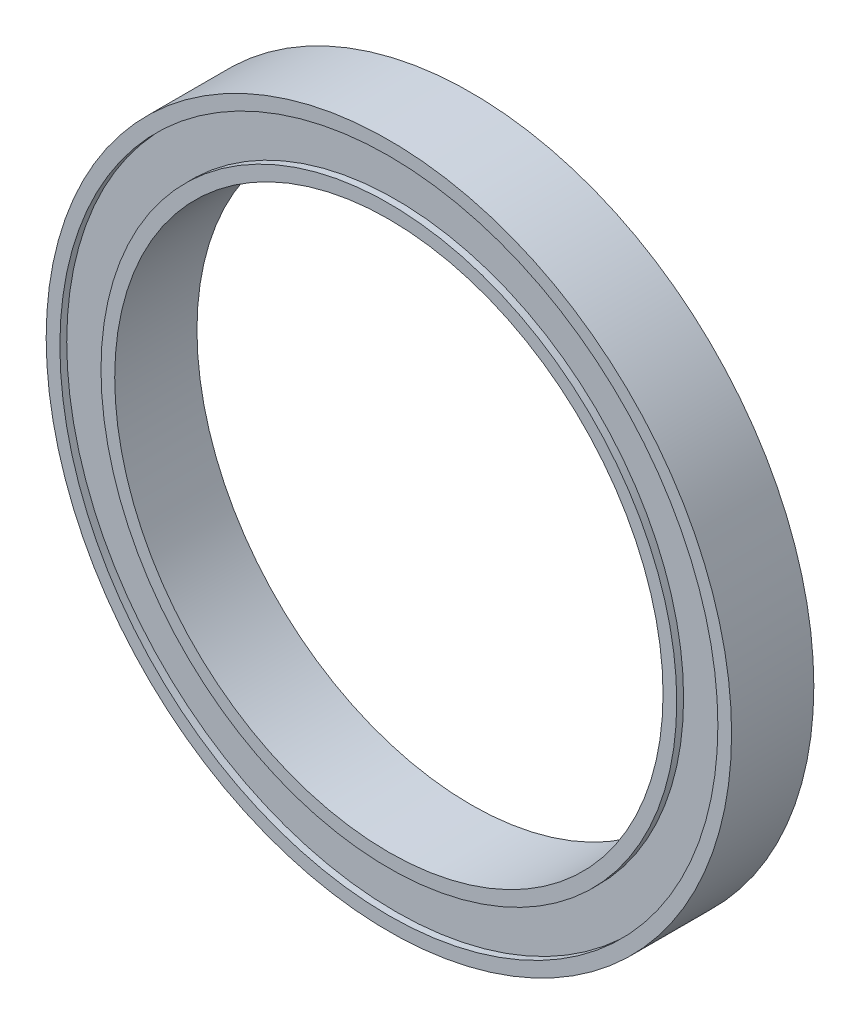
SolidWorks part; units mm, degrees
material "Plain Carbon Steel"
ref_plane "Front Plane" through (0, 0, 0) normal (0, 0, 1) x (1, 0, 0)
ref_plane "Top Plane" through (0, 0, 0) normal (0, 1, 0) x (1, 0, 0)
ref_plane "Right Plane" through (0, 0, 0) normal (1, 0, 0) x (0, 0, -1)
sketch "Sketch1" plane through (0, 0, 0) normal (1, 0, 0) x (0, 0, -1)
  line L0 (0, 0) -> (0, 22.5) construction
  line L1 (0, 0) -> (3, 0) construction
  line L2 (-3, 20) -> (3, 20)
  line L3 (-3, 20) -> (-3, 25)
  line L4 (-3, 25) -> (3, 25)
  line L5 (3, 20) -> (3, 25)
  line L6 (-3, 20) -> (3, 25) construction
  line L7 (-3, 25) -> (3, 20) construction
  dimension "D1" = 20
  dimension "D2" = 25
  dimension "D3" = 6
  dimension "D4" = 5
revolve "Revolve1" add sketch "Sketch1" angle 360 about L1
sketch "Sketch3" plane through (0, 0, 0) normal (1, 0, 0) x (0, 0, -1)
  line L0 (3, 24) -> (2.5, 24)
  line L1 (3, 20) -> (3, 25) construction
  line L2 (2.5, 24) -> (2.5, 21)
  line L3 (2.5, 21) -> (3, 21)
  line L4 (-3, 24) -> (-2.5, 24)
  line L5 (-3, 20) -> (-3, 25) construction
  line L6 (-2.5, 24) -> (-2.5, 21)
  line L7 (-2.5, 21) -> (-3, 21)
  line L8 (-3, 24) -> (-3, 21)
  line L9 (-3, 20) -> (3, 20) construction
  line L10 (3, 24) -> (3, 21)
  dimension "D1" = 0.5
  dimension "D2" = 1
  dimension "D3" = 1
revolve "Cut-Revolve2" cut sketch "Sketch3" angle 360 about L1
fillet "Fillet1" [suppressed] radius 0.5
equation "\"ID\"=40"
equation "\"D1@Sketch1\" = \"ID\" / 2"
equation "\"OD\"=50"
equation "\"D2@Sketch1\"= \"OD\" / 2"
equation "\"B\"=6"
equation "\"D3@Sketch1\"=\"B\""
equation "\"Lip\"=1"
equation "\"D2@Sketch3\"=\"Lip\""
equation "\"D3@Sketch3\"=\"Lip\""
